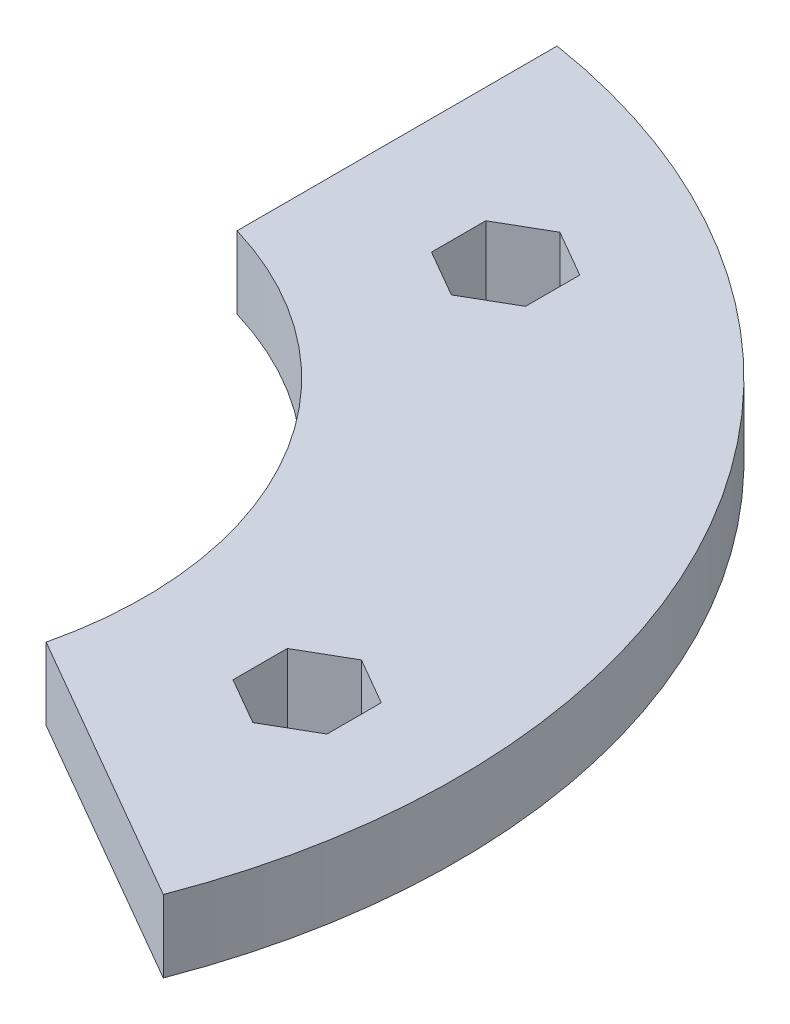
SolidWorks part; units mm, degrees
material "Balsa"
ref_plane "Front Plane" through (0, 0, 0) normal (0, 0, 1) x (1, 0, 0)
ref_plane "Top Plane" through (0, 0, 0) normal (0, 1, 0) x (1, 0, 0)
ref_plane "Right Plane" through (0, 0, 0) normal (1, 0, 0) x (0, 0, -1)
sketch "Sketch1" plane through (0, 0, 0) normal (0, 1, 0) x (1, 0, 0)
  line L0 (-38.3, 0) -> (38.3, 0) construction
  line L1 (0, 38.3) -> (0, -38.3) construction
  line L2 (12.4, -27.4819) -> (15, -28.983)
  line L3 (30, 3.0022) -> (27.4, 1.5011)
  line L4 (27.4, 1.5011) -> (27.4, -1.5011)
  line L5 (27.4, -1.5011) -> (30, -3.0022)
  line L6 (30, -3.0022) -> (32.6, -1.5011)
  line L7 (32.6, -1.5011) -> (32.6, 1.5011)
  line L8 (32.6, 1.5011) -> (30, 3.0022)
  line L9 (12.4, -24.4797) -> (12.4, -27.4819)
  line L10 (15, -22.9785) -> (12.4, -24.4797)
  line L11 (17.6, -24.4797) -> (15, -22.9785)
  line L12 (17.6, -27.4819) -> (17.6, -24.4797)
  line L13 (15, -28.983) -> (17.6, -27.4819)
  line L14 (-17.6, -24.4797) -> (-17.6, -27.4819)
  line L15 (-15, -22.9785) -> (-17.6, -24.4797)
  line L16 (-12.4, -24.4797) -> (-15, -22.9785)
  line L17 (-12.4, -27.4819) -> (-12.4, -24.4797)
  line L18 (-15, -28.983) -> (-12.4, -27.4819)
  line L19 (-17.6, -27.4819) -> (-15, -28.983)
  line L20 (-30, 3.0022) -> (-32.6, 1.5011)
  line L21 (-27.4, 1.5011) -> (-30, 3.0022)
  line L22 (-27.4, -1.5011) -> (-27.4, 1.5011)
  line L23 (-30, -3.0022) -> (-27.4, -1.5011)
  line L24 (-32.6, -1.5011) -> (-30, -3.0022)
  line L25 (-32.6, 1.5011) -> (-32.6, -1.5011)
  line L26 (-12.4, 27.4819) -> (-15, 28.983)
  line L27 (-12.4, 24.4797) -> (-12.4, 27.4819)
  line L28 (-15, 22.9785) -> (-12.4, 24.4797)
  line L29 (-17.6, 24.4797) -> (-15, 22.9785)
  line L30 (-17.6, 27.4819) -> (-17.6, 24.4797)
  line L31 (-15, 28.983) -> (-17.6, 27.4819)
  line L32 (17.6, 24.4797) -> (17.6, 27.4819)
  line L33 (15, 22.9785) -> (17.6, 24.4797)
  line L34 (12.4, 24.4797) -> (15, 22.9785)
  line L35 (12.4, 27.4819) -> (12.4, 24.4797)
  line L36 (15, 28.983) -> (12.4, 27.4819)
  line L37 (17.6, 27.4819) -> (15, 28.983)
  circle A0 centre (0, 0) radius 38.3
  circle A1 centre (30, 0) radius 2.6 construction
  circle A2 centre (0, 0) radius 21
  circle A3 centre (15, -25.9808) radius 2.6 construction
  circle A4 centre (-15, -25.9808) radius 2.6 construction
  circle A5 centre (-30, 0) radius 2.6 construction
  circle A6 centre (-15, 25.9808) radius 2.6 construction
  circle A7 centre (15, 25.9808) radius 2.6 construction
  point P23 (0, 0)
  point P60 (0, 0)
  dimension "D1" = 42
  dimension "D2" = 76.6
  dimension "D3" = 5.2
  dimension "D4" = 30
  dimension "D5" = 6
extrude "Boss-Extrude1" add sketch "Sketch1" along normal blind 4
sketch "Sketch2" plane through (0, 4, 0) normal (0, 1, 0) x (1, 0, 0)
  line L0 (0, 0) -> (0, 45.284) construction
  line L1 (0, 0) -> (52.3716, -30.2368) construction
  line L2 (6, 50.2763) -> (6, 14.2975)
  line L3 (15.382, -1.9526) -> (46.5406, -19.942)
  arc A0 (15.382, -1.9526) -> (6, 14.2975) centre (0, 0) ccw
  arc A2 (6, 50.2763) -> (46.5406, -19.942) centre (0, 0) ccw
  dimension "D1" = 120
  dimension "D2" = 6
  dimension "D3" = 6
extrude "Cut-Extrude1" cut sketch "Sketch2" against normal blind 10 contours L2 A0 L3 A2
